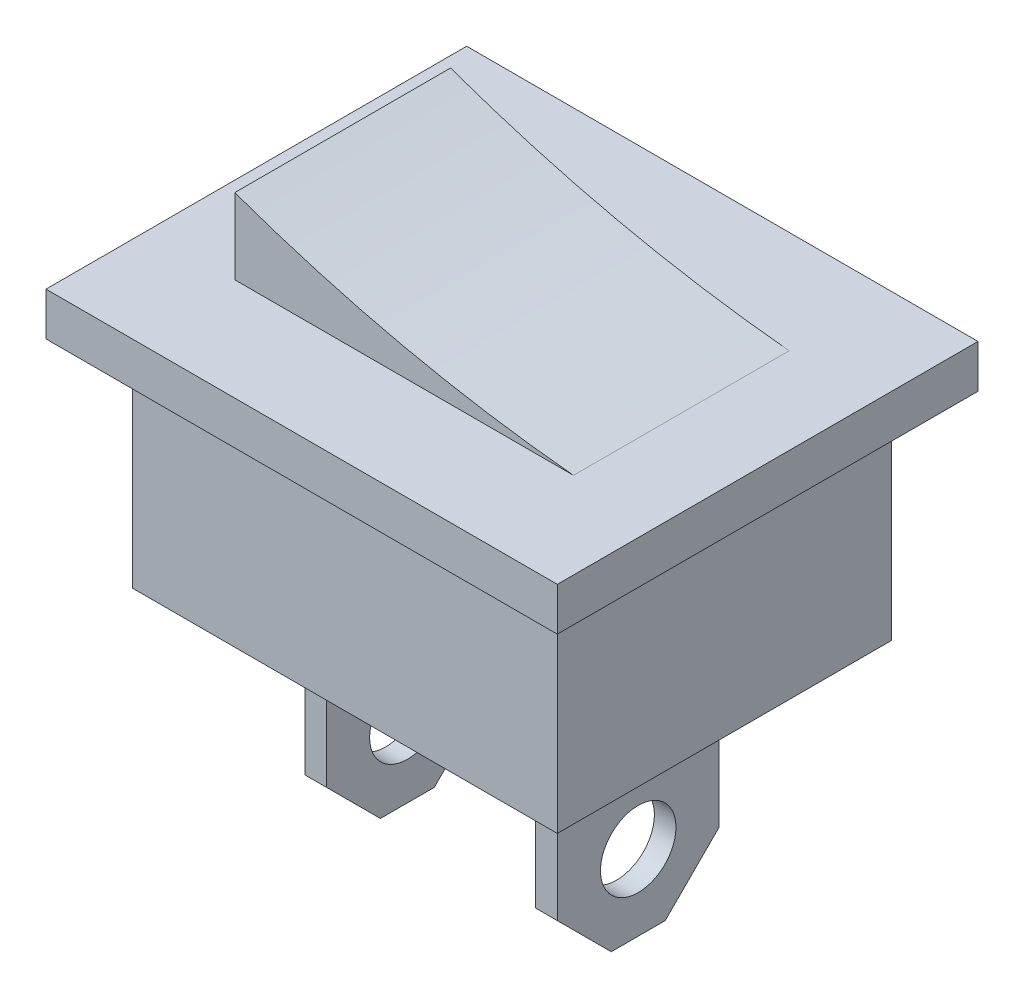
SolidWorks part; units mm, degrees
ref_plane "Alzado" through (0, 0, 0) normal (0, 0, 1) x (1, 0, 0)
ref_plane "Planta" through (0, 0, 0) normal (0, 1, 0) x (1, 0, 0)
ref_plane "Vista lateral" through (0, 0, 0) normal (1, 0, 0) x (0, 0, -1)
sketch "Croquis1" plane through (0, 0, 0) normal (0, 1, 0) x (1, 0, 0)
  line L1 (0, 0) -> (19.7, 0)
  line L2 (0, 0) -> (0, 15.5)
  line L3 (0, 15.5) -> (19.7, 15.5)
  line L4 (19.7, 0) -> (19.7, 15.5)
  dimension "D1" = 19.7
  dimension "D2" = 15.5
extrude "Saliente-Extruir1" add sketch "Croquis1" along normal blind 10
sketch "Croquis2" plane through (0, 10, 0) normal (0, 1, 0) x (1, 0, 0)
  line L8 (-2, 17.5) -> (-2, -2)
  line L9 (-2, -2) -> (21.7, -2)
  line L10 (21.7, -2) -> (21.7, 17.5)
  line L11 (21.7, 17.5) -> (-2, 17.5)
  line L12 (-2, 17.5) -> (-2, -2)
  line L13 (-2, -2) -> (21.7, -2)
  line L14 (21.7, -2) -> (21.7, 17.5)
  line L15 (21.7, 17.5) -> (-2, 17.5)
  dimension "D1" = 2
extrude "Saliente-Extruir2" add sketch "Croquis2" along normal blind 2
ref_plane "Plano1" through (0, 0, -7.75) normal (0, 0, 1) x (1, 0, 0)
sketch "Croquis3" plane through (0, 0, -7.75) normal (0, 0, 1) x (1, 0, 0)
  line L0 (2, 12) -> (2, 15.5)
  line L1 (-2, 12) -> (21.7, 12) construction
  line L2 (2, 12) -> (17.7, 12)
  line L3 (0, 10) -> (0, 0) construction
  line L4 (19.7, 10) -> (19.7, 0) construction
  arc A1 (2, 15.5) -> (17.7, 12) centre (23.8846, 76.7051) ccw
  dimension "D4" = 65
  dimension "D1" = 2
  dimension "D2" = 3.5
  dimension "D3" = 2
extrude "Saliente-Extruir3" add sketch "Croquis3" along normal mid plane 10 separate body
sketch "Croquis4" plane through (0, 0, 0) normal (0, -1, 0) x (1, 0, 0)
  line L0 (5.5, -7.75) -> (-5.5, -7.75) construction
  line L1 (15.7, -4) -> (14.7, -4)
  line L2 (15.7, -4) -> (15.7, -11.5)
  line L3 (15.7, -11.5) -> (14.7, -11.5)
  line L4 (14.7, -4) -> (14.7, -11.5)
  line L5 (15.7, -4) -> (14.7, -11.5) construction
  line L6 (15.7, -11.5) -> (14.7, -4) construction
  line L7 (21.7, 2) -> (21.7, -17.5) construction
  line L8 (5, -4) -> (4, -4)
  line L9 (5, -4) -> (5, -11.5)
  line L10 (5, -11.5) -> (4, -11.5)
  line L11 (4, -4) -> (4, -11.5)
  line L12 (5, -4) -> (4, -11.5) construction
  line L13 (5, -11.5) -> (4, -4) construction
  line L15 (-2, -17.5) -> (-2, 2) construction
  point P0 (15.2, -7.75)
  point P7 (4.5, -7.75)
  point P12 (3.0686, -11.8682)
  dimension "D1" = 7.5
  dimension "D2" = 1
  dimension "D3" = 6.5
  dimension "D4" = 6.5
extrude "Saliente-Extruir4" add sketch "Croquis4" along normal blind 10
chamfer "Chaflán1" distance 2.5 angle 45 4 edges at (4.5, -10, -11.5) (4.5, -10, -4) (15.2, -10, -4) (15.2, -10, -11.5)
sketch "Croquis5" plane through (15.7, 0, 0) normal (1, 0, 0) x (0, 0, -1)
  line L0 (11.5, -7.5) -> (11.5, 0) construction
  line L1 (9, -10) -> (6.5, -10) construction
  circle A0 centre (7.75, -6.5) radius 1.75
  dimension "D1" = 3.5
  dimension "D2" = 3.75
  dimension "D3" = 3.5
extrude "Cortar-Extruir1" cut sketch "Croquis5" against normal up to surface (11.7 mm away) up to face at (4, -5.8333, -7.75)
